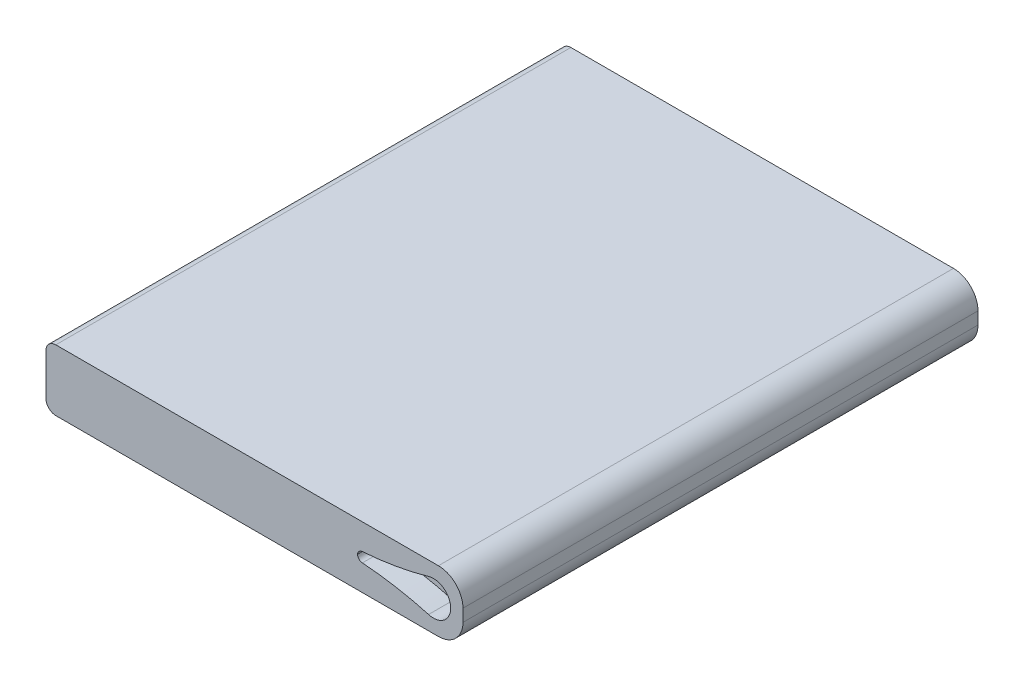
SolidWorks part; units mm, degrees
ref_plane "Front Plane" through (0, 0, 0) normal (0, 0, 1) x (1, 0, 0)
ref_plane "Top Plane" through (0, 0, 0) normal (0, 1, 0) x (1, 0, 0)
ref_plane "Right Plane" through (0, 0, 0) normal (1, 0, 0) x (0, 0, -1)
sketch "Sketch1" plane through (0, 0, 0) normal (0, 1, 0) x (1, 0, 0)
  line L1 (0, 0) -> (80, 0)
  line L2 (0, 0) -> (0, 105)
  line L3 (0, 105) -> (80, 105)
  line L4 (80, 0) -> (80, 105)
  line L5 (80, 105) -> (-5, 105)
  line L6 (80, 105) -> (80, 0)
  line L7 (80, 0) -> (-5, 0)
  line L8 (-5, 105) -> (-5, 0)
  dimension "D1" = 105
  dimension "D2" = 80
  dimension "D3" = 85
extrude "Boss-Extrude1" add sketch "Sketch1" along normal blind 12.5 contours L2 L1 L4 L3 | L6 L5 L8 L7
sketch "Sketch2" plane through (0, 0, 0) normal (0, 0, 1) x (1, 0, 0)
  line L0 (80, 6.25) -> (74, 6.25)
  line L1 (80, 12.5) -> (80, 0) construction
  line L2 (80, 12.5) -> (73, 12.5)
  line L3 (-5, 12.5) -> (80, 12.5) construction
  line L4 (73, 12.5) -> (73, 9.6041)
  line L5 (73, 9.6041) -> (73, 2.8959)
  line L6 (77.5, 6.25) -> (58.5, 6.25)
  line L7 (58.5, 6.25) -> (59.5, 6.25)
  circle A0 centre (74, 6.25) radius 3.5
  arc A1 (58.5, 6.25) -> (59.5, 7.25) centre (59.574, 6.176) cw
  arc A2 (58.5, 6.25) -> (59.5, 5.25) centre (59.5813, 6.3313) ccw
  arc A3 (59.5, 5.25) -> (73, 2.8959) centre (54.2313, -64.8501) cw
  arc A4 (59.5, 7.25) -> (73, 9.6041) centre (54.956, 73.1943) ccw
  dimension "D1" = 7
  dimension "D2" = 7
  dimension "D3" = 19
  dimension "D4" = 1
  dimension "D5" = 1
  dimension "D6" = 1
  dimension "D7" = 6
extrude "Cut-Extrude1" cut sketch "Sketch2" against normal blind 5 contours L0 A0 L5 L6 | L5 A0 L0 L6 | L6 A0 L5 | L5 A0 L6 | A2 A3 A0 L6 | A4 A1 L6 A0
sketch "Sketch5" plane through (0, 0, 0) normal (1, 0, 0) x (0, 0, -1)
  line L0 (0, 12.5) -> (114.4818, 12.5) construction
ref_plane "Plane1" through (0, 0, -105) normal (0, 0, 1) x (1, 0, 0)
fillet "Fillet1" radius 5 1 edges at (80, 0, -52.5)
fillet "Fillet2" radius 5 1 edges at (80, 12.5, -52.5)
fillet "Fillet3" radius 2 2 edges at (-5, 0, -52.5) (-5, 12.5, -52.5)
